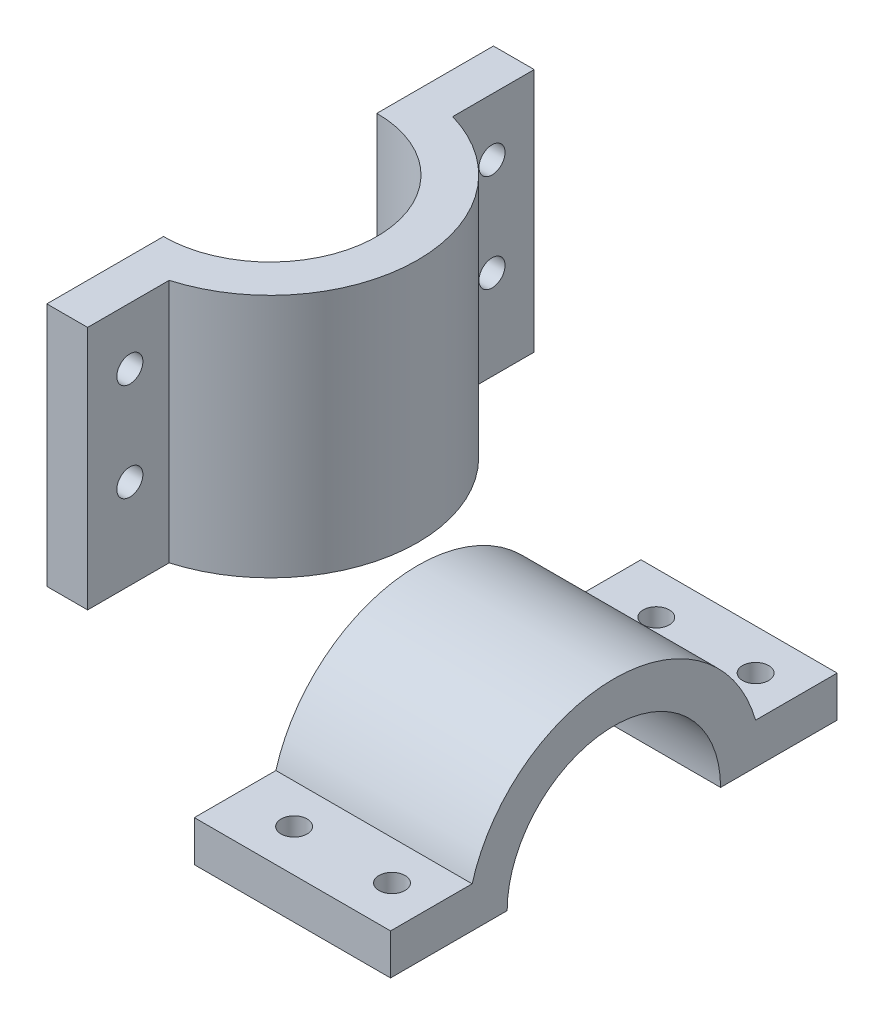
SolidWorks part; units mm, degrees
ref_plane "Front Plane" through (0, 0, 0) normal (0, 0, 1) x (1, 0, 0)
ref_plane "Top Plane" through (0, 0, 0) normal (0, 1, 0) x (1, 0, 0)
ref_plane "Right Plane" through (0, 0, 0) normal (1, 0, 0) x (0, 0, -1)
sketch "Sketch2" plane through (0, 0, 300.4259) normal (0, 0, 1) x (1, 0, 0)
  line L0 (-749.5, -152.4) -> (-707.3619, -152.4)
  line L1 (-749.5, -182.4) -> (-749.5, -152.4) construction
  line L2 (-707.3619, -152.4) -> (-707.3619, -202.9047)
  line L3 (-755.5887, -152.4) -> (-749.5, -152.4) construction
  line L4 (-749.5, -152.4) -> (-749.5, -202.9047)
  line L5 (-749.5, -202.9047) -> (-707.3619, -202.9047)
sketch "Sketch5" plane through (0, -152.4, 0) normal (0, 1, 0) x (1, 0, 0)
  line L0 (-749.5, -256.025) -> (-749.5, -259.969)
  line L1 (-749.5, -290.075) -> (-749.5, -300.4259)
  line L2 (-749.5, -256.025) -> (-749.5, -245.6741)
  line L3 (-749.5, -245.6741) -> (-744.5, -245.6741)
  line L5 (-744.5, -245.6741) -> (-744.5, -255.6741)
  line L6 (-749.5, -300.4259) -> (-744.5, -300.4259)
  line L7 (-744.5, -300.4259) -> (-744.5, -290.4259)
  line L8 (-749.5, -290.075) -> (-749.5, -286.131)
  line L10 (-749.5, -245.6741) -> (-749.5, -260.223) construction
  circle A0 centre (-749.5, -273.05) radius 18.081 construction
  arc A1 (-744.5, -290.4259) -> (-744.5, -255.6741) centre (-749.5, -273.05) ccw
  circle A2 centre (-749.5, -273.05) radius 13.081
  arc A3 (-749.5, -286.131) -> (-749.5, -259.969) centre (-749.5, -273.05) ccw
  circle A4 centre (-749.5, -273.05) radius 13.081 construction
  dimension "D3" = 5
  dimension "D4" = 10
  dimension "D1" = 0
  dimension "D2" = 5
extrude "Boss-Extrude2" add sketch "Sketch5" against normal blind 30
sketch "Sketch6" plane through (-707.3619, 0, 0) normal (1, 0, 0) x (0, 0, -1)
  line L2 (-291.131, -202.9047) -> (-300.4259, -202.9047)
  line L3 (-300.4259, -202.9047) -> (-300.4259, -197.9047)
  line L4 (-300.4259, -197.9047) -> (-290.4259, -197.9047)
  line L5 (-254.969, -202.9047) -> (-245.6741, -202.9047)
  line L6 (-245.6741, -202.9047) -> (-245.6741, -197.9047)
  line L7 (-245.6741, -197.9047) -> (-255.6741, -197.9047)
  line L8 (-291.131, -202.9047) -> (-286.131, -202.9047)
  line L9 (-259.969, -202.9047) -> (-254.969, -202.9047)
  arc A1 (-255.6741, -197.9047) -> (-290.4259, -197.9047) centre (-273.05, -202.9047) ccw
  circle A2 centre (-273.05, -202.9047) radius 13.081
  arc A3 (-259.969, -202.9047) -> (-286.131, -202.9047) centre (-273.05, -202.9047) ccw
  circle A4 centre (-273.05, -202.9047) radius 13.081 construction
  circle A7 centre (-273.05, -202.9047) radius 18.081 construction
  dimension "D3" = 5
  dimension "D1" = 0
  dimension "D4" = 10
  dimension "D2" = 5
extrude "Boss-Extrude3" add sketch "Sketch6" against normal up to vertex (24.0571 mm away) separate body
sketch "Sketch8" plane through (-749.5, 0, 0) normal (-1, 0, 0) x (0, 0, 1)
  circle A0 centre (295.2504, -159.4) radius 1.6
  circle A1 centre (295.2504, -171.4) radius 1.6
  circle A2 centre (250.8496, -171.4) radius 1.6
  circle A3 centre (250.8496, -159.4) radius 1.6
  dimension "D1" = 3.2
extrude "Cut-Extrude3" cut sketch "Sketch8" against normal through all
sketch "Sketch10" plane through (0, -202.9047, 0) normal (0, -1, 0) x (1, 0, 0)
  circle A0 centre (-724.3619, 295.2504) radius 1.6
  circle A1 centre (-712.3619, 295.2504) radius 1.6
  circle A2 centre (-712.3619, 250.6741) radius 1.6
  circle A3 centre (-724.3619, 250.8496) radius 1.6
  dimension "D1" = 3.2
extrude "Cut-Extrude4" cut sketch "Sketch10" against normal through all
sketch3d "3DSketch1"
  line L0 (-749.5, -202.9047, 300.4259) -> (-749.5, -202.9047, 224.2259)
  dimension "D1" = 76.2
